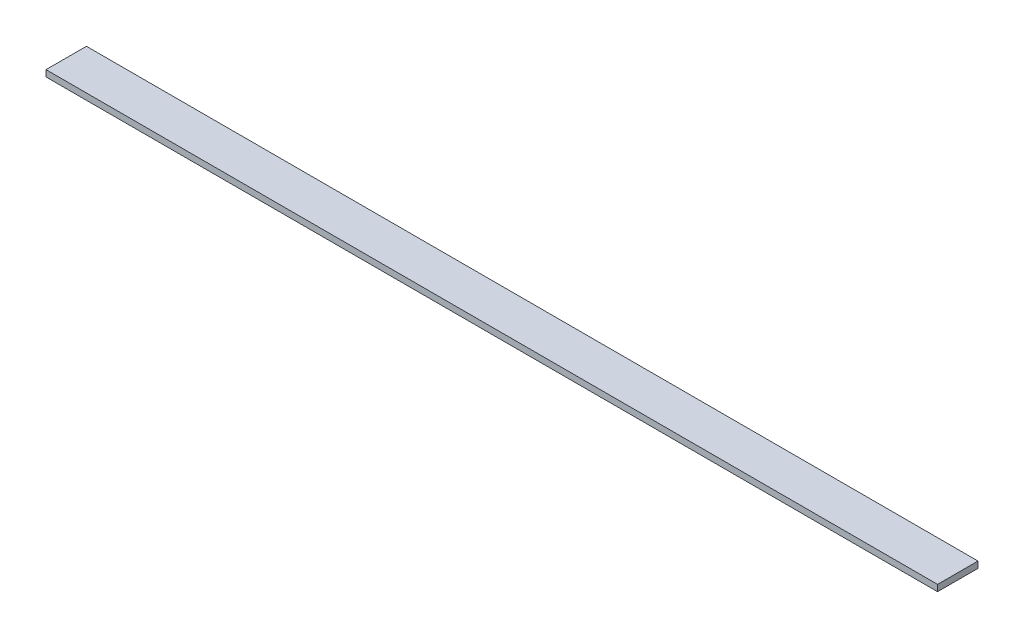
SolidWorks part; units mm, degrees
ref_plane "Alzado" through (0, 0, 0) normal (0, 0, 1) x (1, 0, 0)
ref_plane "Planta" through (0, 0, 0) normal (0, 1, 0) x (1, 0, 0)
ref_plane "Vista lateral" through (0, 0, 0) normal (1, 0, 0) x (0, 0, -1)
sketch "Croquis1" plane through (0, 0, 0) normal (0, 1, 0) x (1, 0, 0)
  line L1 (0, 0) -> (-280, 0)
  line L2 (0, 0) -> (0, -12.7)
  line L3 (0, -12.7) -> (-280, -12.7)
  line L4 (-280, 0) -> (-280, -12.7)
  dimension "D1" = 12.7
  dimension "D2" = 280
extrude "Saliente-Extruir1" add sketch "Croquis1" along normal blind 2
